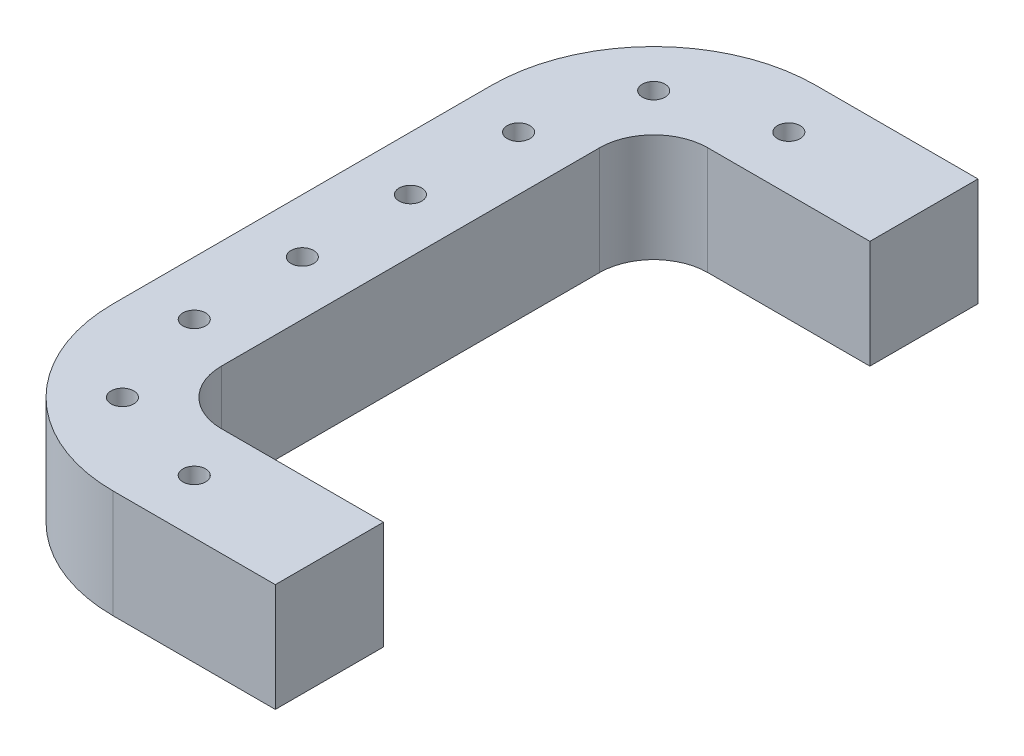
SolidWorks part; units mm, degrees
material "Custom Plastic"
ref_plane "Front Plane" through (0, 0, 0) normal (0, 0, 1) x (1, 0, 0)
ref_plane "Top Plane" through (0, 0, 0) normal (0, 1, 0) x (1, 0, 0)
ref_plane "Right Plane" through (0, 0, 0) normal (1, 0, 0) x (0, 0, -1)
sketch "Sketch1" plane through (0, 0, 0) normal (0, 1, 0) x (1, 0, 0)
  line L0 (0, 0) -> (0, 30) construction
  line L1 (20, 50) -> (50, 50) construction
  line L2 (10, 0) -> (10, 30)
  line L3 (20, 40) -> (50, 40)
  line L4 (-10, 0) -> (-10, 30)
  line L5 (20, 60) -> (50, 60)
  line L6 (10, 0) -> (-10, 0)
  line L7 (50, 40) -> (50, 60)
  arc A0 (0, 30) -> (20, 50) centre (20, 30) cw construction
  arc A1 (10, 30) -> (20, 40) centre (20, 30) cw
  arc A2 (-10, 30) -> (20, 60) centre (20, 30) cw
  point P6 (0, 50)
  dimension "D2" = 20
  dimension "D1" = 50
  dimension "D3" = 10
  dimension "D4" = 10
extrude "Boss-Extrude1" add sketch "Sketch1" along normal mid plane 20
sketch "Sketch3" plane through (0, 10, 0) normal (0, 1, 0) x (1, 0, 0)
  line L0 (-10, 30) -> (-10, 0) construction
  line L1 (10, 0) -> (-10, 0)
  line L2 (10, 0) -> (10, -5)
  line L3 (10, -5) -> (-10, -5)
  line L4 (-10, 0) -> (-10, -5)
  line L5 (50, 60) -> (20, 60) construction
  dimension "D1" = 65
extrude "Boss-Extrude2" add sketch "Sketch3" against normal up to surface (20 mm away) up to face at (16.4645, -10, -33.5355)
sketch "Sketch2" plane through (0, 10, 0) normal (0, 1, 0) x (1, 0, 0)
  line L0 (12.9289, 37.0711) -> (-1.2132, 51.2132) construction
  line L1 (0, 0) -> (0, 50) construction
  line L3 (0, 0) -> (0, -5) construction
  line L4 (-10, -5) -> (10, -5) construction
  arc A0 (20, 40) -> (10, 30) centre (20, 30) ccw construction
  arc A1 (20, 60) -> (-10, 30) centre (20, 30) ccw construction
  circle A2 centre (5.8579, 44.1421) radius 2.1
  circle A3 centre (0, 25) radius 2.1
  circle A5 centre (25, 50) radius 2.1
  circle A6 centre (0, 5) radius 2.1
  dimension "D1" = 4.2
  dimension "D2" = 10
  dimension "D3" = 20
  dimension "D4" = 4.2
extrude "Cut-Extrude1" cut sketch "Sketch2" against normal through all
mirror "Mirror1" about plane through (10, -30.6155, 5) normal (0, 0, 1) of bodies 102
